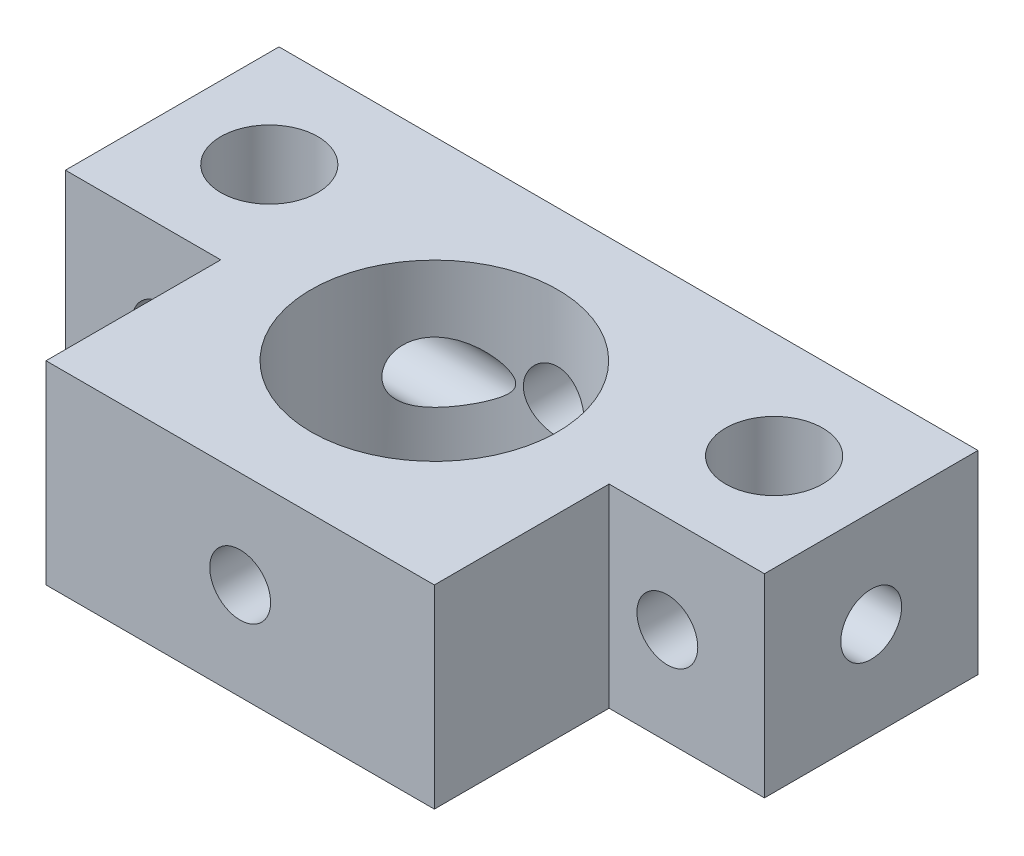
SolidWorks part; units mm, degrees
ref_plane "Front Plane" through (0, 0, 0) normal (0, 0, 1) x (1, 0, 0)
ref_plane "Top Plane" through (0, 0, 0) normal (0, 1, 0) x (1, 0, 0)
ref_plane "Right Plane" through (0, 0, 0) normal (1, 0, 0) x (0, 0, -1)
ref_plane "Plane1" through (0, -5, 0) normal (0, -1, 0) x (1, 0, 0)
sketch "Sketch1" plane through (0, -5, 0) normal (0, -1, 0) x (1, 0, 0)
  line L0 (9, 10) -> (-9, 10)
  line L1 (-9, 10) -> (-9, 0)
  line L2 (-9, 0) -> (9, 0)
  line L3 (9, 0) -> (9, 10)
extrude "Boss-Extrude1" add sketch "Sketch1" against normal blind 5
sketch "Sketch2" plane through (0, 0, 0) normal (0, 1, 0) x (-1, 0, 0)
  line L0 (5, 5.5) -> (9, 5.5)
  line L1 (9, 5.5) -> (9, 10)
  line L2 (9, 10) -> (5, 10)
  line L3 (5, 10) -> (5, 5.5)
extrude "Cut-Extrude1" cut sketch "Sketch2" against normal through all
sketch "Sketch3" plane through (0, 0, 0) normal (0, 1, 0) x (-1, 0, 0)
  line L0 (-5, 5.5) -> (-5, 10)
  line L1 (-5, 10) -> (-9, 10)
  line L2 (-9, 10) -> (-9, 5.5)
  line L3 (-9, 5.5) -> (-5, 5.5)
extrude "Cut-Extrude2" cut sketch "Sketch3" against normal through all
hole_wizard "Ø2.5 (2.5) Diameter Hole1" positions "Sketch5" profile "Sketch4" hole size "Ø2.5" standard "ANSI Metric"
sketch "Sketch5" plane through (0, 0, 0) normal (0, 1, 0) x (1, 0, 0)
  point P0 (6.5, -2.75)
  point P1 (-6.5, -2.75)
sketch "Sketch4" plane through (6.5, 0, 2.75) normal (1, 0, 0) x (0, 0, 1)
  line L0 (0, 0) -> (0, 5)
  line L1 (0, 5) -> (1.25, 5)
  line L2 (1.25, 5) -> (1.25, 0)
  line L5 (1.25, 0) -> (0, 0)
  line L11 (0, -6.35) -> (0, 107.95) construction
  dimension "Thru Hole Dia." = 2.5
  dimension "Thru Hole Depth" = 5
hole_wizard "Hole1" positions "Sketch7" profile "Sketch6" legacy
sketch "Sketch7" plane through (9, 0, 0) normal (1, 0, 0) x (0, 0, -1)
  point P0 (-2.75, -2.5)
sketch "Sketch6" plane through (9, -2.5, 2.75) normal (0, 1, 0) x (0, 0, -1)
  line L0 (0, 0) -> (0, 19.526)
  line L1 (0, 19.526) -> (0.7835, 19.526)
  line L2 (0.7835, 19.526) -> (0.7835, 0)
  line L3 (0.7835, 0) -> (0, 0)
  line L4 (0, 110) -> (0, -10) construction
  dimension "Diameter" = 1.567
  dimension "Depth" = 19.526
hole_wizard "Hole2" positions "Sketch9" profile "Sketch8" legacy
sketch "Sketch9" plane through (0, 0, 5.5) normal (0, 0, 1) x (1, 0, 0)
  point P0 (6.5, -2.5)
  point P1 (-6.5, -2.5)
sketch "Sketch8" plane through (6.5, -2.5, 5.5) normal (1, 0, 0) x (0, -1, 0)
  line L0 (0, 0) -> (0, 7.276)
  line L1 (0, 7.276) -> (0.7835, 7.276)
  line L2 (0.7835, 7.276) -> (0.7835, 0)
  line L3 (0.7835, 0) -> (0, 0)
  line L4 (0, 110) -> (0, -10) construction
  dimension "Diameter" = 1.567
  dimension "Depth" = 7.276
hole_wizard "Hole3" positions "Sketch11" profile "Sketch10" legacy
sketch "Sketch11" plane through (0, 0, 0) normal (0, 1, 0) x (1, 0, 0)
  point P0 (0, -5)
sketch "Sketch10" plane through (0, 0, 5) normal (1, 0, 0) x (0, 0, 1)
  line L0 (0, 0) -> (0, 5)
  line L1 (0, 5) -> (3.175, 5)
  line L2 (3.175, 5) -> (3.175, 0)
  line L3 (3.175, 0) -> (0, 0)
  line L4 (0, 110) -> (0, -10) construction
  dimension "Diameter" = 6.35
  dimension "Depth" = 5
hole_wizard "Hole4" positions "Sketch13" profile "Sketch12" legacy
sketch "Sketch13" plane through (0, 0, 10) normal (0, 0, 1) x (1, 0, 0)
  point P0 (0, -2.5)
sketch "Sketch12" plane through (0, -2.5, 10) normal (1, 0, 0) x (0, -1, 0)
  line L0 (0, 0) -> (0, 11.9232)
  line L1 (0, 11.9232) -> (0.7835, 11.9232)
  line L2 (0.7835, 11.9232) -> (0.7835, 0)
  line L3 (0.7835, 0) -> (0, 0)
  line L4 (0, 110) -> (0, -10) construction
  dimension "Diameter" = 1.567
  dimension "Depth" = 11.9232
